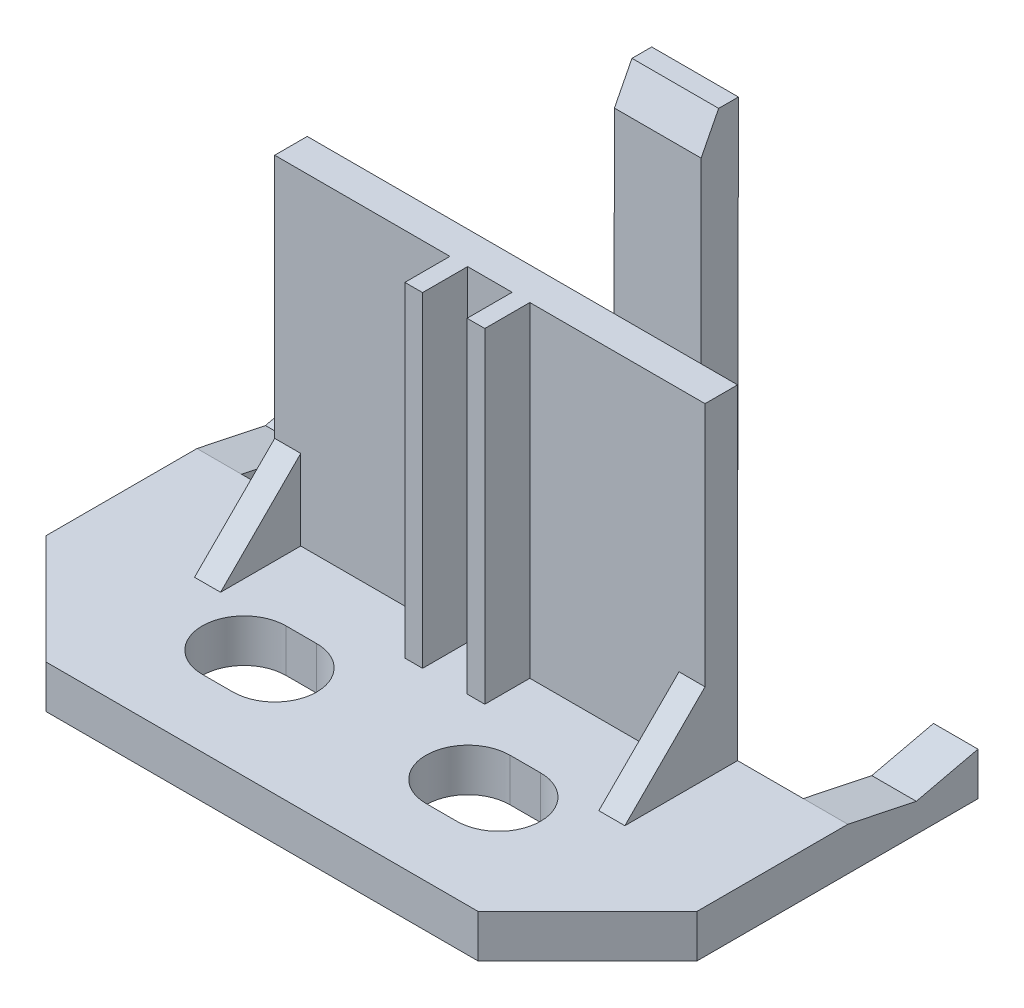
SolidWorks part; units mm, degrees
material "ABS"
ref_plane "Front Plane" through (0, 0, 0) normal (0, 0, 1) x (1, 0, 0)
ref_plane "Top Plane" through (0, 0, 0) normal (0, 1, 0) x (1, 0, 0)
ref_plane "Right Plane" through (0, 0, 0) normal (1, 0, 0) x (0, 0, -1)
sketch "Sketch1" plane through (0, 0, 0) normal (0, 1, 0) x (1, 0, 0)
  line L0 (10.541, 0) -> (15.875, 5.334)
  line L1 (-15.875, 12.7) -> (15.875, 12.7)
  line L2 (-15.875, 12.7) -> (-15.875, 0) construction
  line L3 (-15.875, 0) -> (15.875, 0) construction
  line L4 (15.875, 12.7) -> (15.875, 0) construction
  line L5 (-10.541, 0) -> (-15.875, 5.334)
  line L6 (0, 0) -> (0, 12.7) construction
  line L7 (-15.875, 12.7) -> (-15.875, 5.334)
  line L8 (-10.541, 0) -> (10.541, 0)
  line L9 (15.875, 12.7) -> (15.875, 5.334)
  line L10 (-6.2103, 5.334) -> (-4.7117, 5.334) construction
  line L11 (-6.2103, 7.3787) -> (-4.7117, 7.3787)
  line L12 (-6.2103, 3.2893) -> (-4.7117, 3.2893)
  line L13 (6.2103, 5.334) -> (4.7117, 5.334) construction
  line L14 (6.2103, 7.3787) -> (4.7117, 7.3787)
  line L15 (6.2103, 3.2893) -> (4.7117, 3.2893)
  arc A0 (-6.2103, 7.3787) -> (-6.2103, 3.2893) centre (-6.2103, 5.334) ccw
  arc A1 (-4.7117, 3.2893) -> (-4.7117, 7.3787) centre (-4.7117, 5.334) ccw
  arc A2 (6.2103, 7.3787) -> (6.2103, 3.2893) centre (6.2103, 5.334) cw
  arc A3 (4.7117, 3.2893) -> (4.7117, 7.3787) centre (4.7117, 5.334) cw
  point P4 (0, 0)
  point P14 (-5.461, 5.334)
  point P19 (-8.255, 5.334)
  point P20 (-2.667, 5.334)
  point P24 (5.461, 5.334)
  dimension "D1" = 31.75
  dimension "D2" = 12.7
  dimension "D3" = 5.334
  dimension "D4" = 5.334
  dimension "D5" = 5.588
  dimension "D6" = 4.0894
  dimension "D7" = 5.334
  dimension "D8" = 7.62
extrude "Boss-Extrude1" add sketch "Sketch1" along normal blind 2.0955
sketch "Sketch2" plane through (0, 2.0955, 0) normal (0, 1, 0) x (1, 0, 0)
  line L0 (15.875, 12.7) -> (-15.875, 12.7) construction
  line L1 (-10.4966, 12.7) -> (10.4966, 12.7)
  line L2 (-10.4966, 12.7) -> (-10.4966, 11.1125)
  line L3 (-10.4966, 11.1125) -> (10.4966, 11.1125)
  line L4 (10.4966, 12.7) -> (10.4966, 11.1125)
  point P6 (0, 12.7)
  point P7 (0, 12.7)
  dimension "D1" = 20.9931
  dimension "D2" = 1.5875
extrude "Boss-Extrude2" add sketch "Sketch2" along normal blind 15.875
sketch "Sketch4" plane through (-10.4966, 0, 0) normal (-1, 0, 0) x (0, 0, 1)
  line L0 (-11.1125, 6.0071) -> (-7.2009, 2.0955)
  line L1 (-11.1125, 17.9705) -> (-11.1125, 2.0955) construction
  line L2 (-7.2009, 2.0955) -> (-11.1125, 2.0955)
  line L3 (-11.1125, 2.0955) -> (-11.1125, 6.0071)
  line L4 (-12.7, 2.0955) -> (-11.1125, 2.0955) construction
  dimension "D1" = 3.9116
  dimension "D2" = 3.9116
extrude "Boss-Extrude3" add sketch "Sketch4" against normal blind 1.27
sketch "Sketch5" plane through (0, 17.9705, 0) normal (0, 1, 0) x (1, 0, 0)
  line L0 (-10.4966, 11.1125) -> (10.4966, 11.1125) construction
  line L1 (-1.9495, 11.1125) -> (-1.0858, 11.1125)
  line L2 (-1.9495, 11.1125) -> (-1.9494, 8.9154)
  line L3 (-1.9494, 8.9154) -> (-1.0858, 8.9154)
  line L4 (-1.0858, 11.1125) -> (-1.0858, 8.9154)
  line L5 (-10.4966, 12.7) -> (-10.4966, 11.1125) construction
  dimension "D1" = 2.1971
  dimension "D2" = 0.8636
  dimension "D3" = 8.5471
extrude "Boss-Extrude4" add sketch "Sketch5" against normal up to surface (15.875 mm away) up to face at (-5.461, 2.0955, -5.334)
sketch "Sketch6" plane through (0, 0, -12.7) normal (0, 0, -1) x (-1, 0, 0)
  line L1 (-10.4966, 17.9705) -> (10.4965, 17.9705) construction
  line L2 (0, 17.9705) -> (0, 0) construction
  circle A0 centre (4.6037, 14.6431) radius 1.0795
  point P7 (0, 0)
  dimension "D1" = 2.159
  dimension "D2" = 9.2075
  dimension "D3" = 3.3274
extrude "Boss-Extrude5" add sketch "Sketch6" along normal blind 2.032
sketch "Sketch7" plane through (-15.875, 0, 0) normal (-1, 0, 0) x (0, 0, 1)
  line L0 (-12.7, 0) -> (-19.05, 0)
  line L1 (-19.05, 0) -> (-19.05, 2.0955)
  line L2 (-19.05, 2.0955) -> (-16.0401, 1.397)
  line L3 (-16.0401, 1.397) -> (-12.7, 2.0955)
  line L5 (-12.7, 2.0955) -> (-12.7, 0)
  dimension "D1" = 6.35
  dimension "D2" = 1.397
  dimension "D3" = 3.0099
extrude "Boss-Extrude6" add sketch "Sketch7" against normal blind 2.1717
mirror "Mirror1" about plane through (0, 0, 0) normal (1, 0, 0) of "Boss-Extrude6", "Boss-Extrude3", "Boss-Extrude4", "Boss-Extrude5"
sketch "Sketch8" plane through (0, 0, 0) normal (0, -1, 0) x (-1, 0, 0)
  line L0 (-13.7033, 12.7) -> (13.7033, 12.7) construction
  line L1 (-2.1146, 12.7) -> (2.1146, 12.7)
  line L2 (-2.1146, 12.7) -> (-2.1146, 21.082)
  line L3 (-2.1146, 21.082) -> (2.1146, 21.082)
  line L4 (2.1146, 12.7) -> (2.1146, 21.082)
  point P6 (0, 12.7)
  point P7 (0, 12.7)
  dimension "D1" = 4.2291
  dimension "D2" = 8.382
extrude "Boss-Extrude7" add sketch "Sketch8" against normal up to surface (2.0955 mm away) up to face at (-5.461, 2.0955, -5.334)
sketch "Sketch9" plane through (0, 0, 0) normal (1, 0, 0) x (0, 0, -1)
  line L0 (21.082, 2.0955) -> (21.1237, 21.7297)
  line L1 (21.1237, 21.7297) -> (20.1585, 21.7317)
  line L2 (20.1585, 21.7317) -> (19.304, 20.0572)
  line L3 (19.304, 20.0572) -> (19.2659, 2.0955)
  line L4 (21.082, 2.0955) -> (12.7, 2.0955) construction
  line L5 (19.2659, 2.0955) -> (21.082, 2.0955)
  line L6 (19.2849, 11.0763) -> (21.101, 11.0725) construction
  dimension "D1" = 1.8161
  dimension "D2" = 19.6342
  dimension "D3" = 0.9652
  dimension "D4" = 1.6764
  dimension "D5" = 6.604
extrude "Boss-Extrude8" add sketch "Sketch9" along normal mid plane 4.2291
